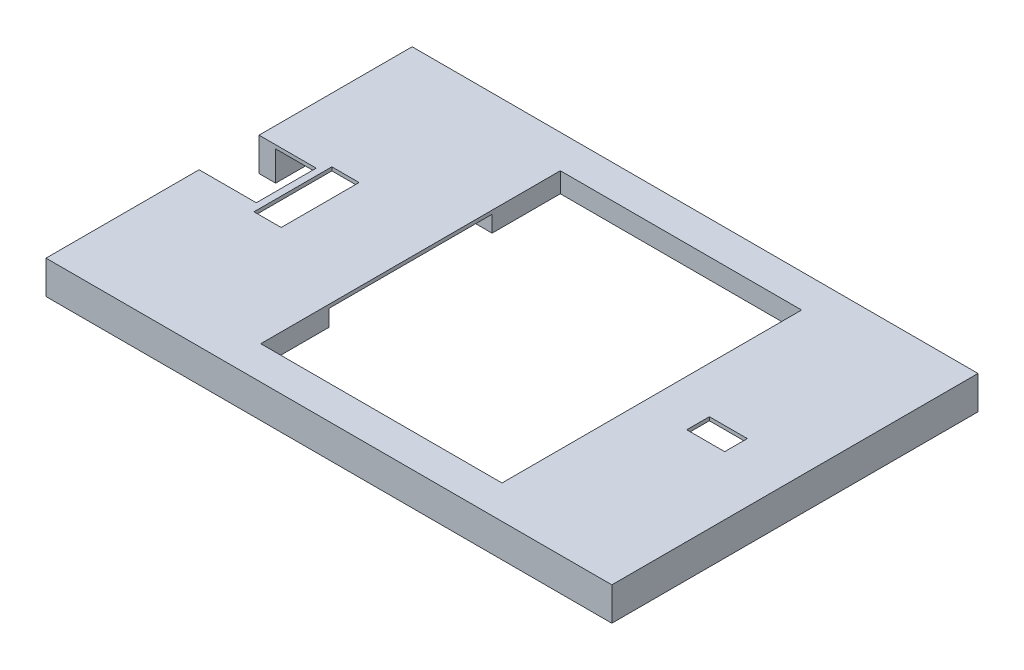
SolidWorks part; units mm, degrees
ref_plane "Front Plane" through (0, 0, 0) normal (0, 0, 1) x (1, 0, 0)
ref_plane "Top Plane" through (0, 0, 0) normal (0, 1, 0) x (1, 0, 0)
ref_plane "Right Plane" through (0, 0, 0) normal (1, 0, 0) x (0, 0, -1)
sketch "Sketch1" plane through (0, 0, 0) normal (0, 1, 0) x (1, 0, 0)
  line L0 (1.24, -32) -> (8.59, -32) construction
  line L1 (0, 0) -> (85, 0)
  line L2 (0, 0) -> (0, -55)
  line L3 (0, -55) -> (85, -55)
  line L4 (85, 0) -> (85, -55)
  line L5 (8.59, -23) -> (0, -23)
  line L6 (8.59, -23) -> (8.59, -32)
  line L7 (8.59, -32) -> (0, -32)
  line L8 (0, -23) -> (0, -32)
  line L9 (12.68, -32.35) -> (9.59, -32.35) construction
  line L10 (12.68, -32.35) -> (12.68, -22.65) construction
  line L11 (12.68, -22.65) -> (9.59, -22.65) construction
  line L12 (9.59, -32.35) -> (9.59, -22.65)
  line L13 (12.68, -22.65) -> (10.48, -22.65) construction
  line L14 (9.59, -22.65) -> (9.59, -21.65)
  line L15 (9.59, -21.65) -> (13.68, -21.65)
  line L16 (13.68, -21.65) -> (13.68, -33.35)
  line L17 (13.68, -33.35) -> (9.59, -33.35)
  line L18 (9.59, -33.35) -> (9.59, -32.35)
  line L19 (76.15, -25.8) -> (70.45, -25.8) construction
  line L20 (76.15, -25.8) -> (70.45, -25.8)
  line L21 (76.15, -25.8) -> (76.15, -29.2)
  line L22 (76.15, -29.2) -> (70.45, -29.2)
  line L23 (70.45, -25.8) -> (70.45, -29.2)
  line L24 (76.15, -29.2) -> (76.15, -25.8) construction
  line L25 (25.26, -36.5) -> (25.26, -18.5) construction
  line L26 (27.26, -5) -> (63.5, -5)
  line L27 (27.26, -5) -> (27.26, -50)
  line L28 (27.26, -50) -> (63.5, -50)
  line L29 (63.5, -5) -> (63.5, -50)
  line L30 (65.5, -31.75) -> (65.5, -36.5) construction
  dimension "D1" = 85
  dimension "D2" = 55
  dimension "D3" = 1
  dimension "D4" = 1
  dimension "D5" = 1
  dimension "D6" = 1
  dimension "D7" = 5
  dimension "D8" = 5
  dimension "D9" = 2
  dimension "D10" = 2
extrude "Boss-Extrude1" add sketch "Sketch1" along normal blind 3 contours L6 L7 L2 L3 L4 L1 L5 L23 L20 L21 L22 L17 L18 L12 L14 L15 L16 L26 L29 L28 L27
sketch "Sketch3" plane through (63.5, 0, 0) normal (-1, 0, 0) x (0, 0, 1)
  line L0 (36.5, 0.3152) -> (37.75, 0.3152) construction
  line L1 (31.75, 0.3152) -> (36.5, 0.3152) construction
  line L2 (18.5, 0.3152) -> (23.13, 0.3152) construction
  line L3 (17.25, 0.3152) -> (18.5, 0.3152) construction
  line L4 (36.5, 0.3152) -> (37.75, 0.3152) construction
  line L5 (31.75, 0.3152) -> (36.5, 0.3152) construction
  line L6 (18.5, 0.3152) -> (23.13, 0.3152) construction
  line L7 (17.25, 0.3152) -> (18.5, 0.3152) construction
  line L8 (5, 0) -> (50, 0) construction
  line L9 (15.25, 0) -> (39.75, 0)
  line L10 (15.25, 0) -> (15.25, 2.4652)
  line L11 (15.25, 2.4652) -> (39.75, 2.4652)
  line L12 (39.75, 0) -> (39.75, 2.4652)
  line L13 (26.45, 1.9652) -> (22.65, 1.9652) construction
  line L14 (26.45, 1.9652) -> (22.65, 1.9652)
  dimension "D1" = 2
  dimension "D2" = 2
  dimension "D3" = 0.5
extrude "Cut-Extrude1" cut sketch "Sketch3" against normal blind 19 and the other way blind 61
sketch "Sketch4" plane through (0, 0, 0) normal (0, -1, 0) x (1, 0, 0)
  line L0 (2.5, 32) -> (0, 32) construction
  line L1 (2.5, 23) -> (0, 23) construction
  line L2 (85, 0) -> (85, 55) construction
  line L3 (0, 55) -> (85, 55) construction
  line L4 (0, 32) -> (0, 55) construction
  line L5 (0, 0) -> (85, 0) construction
  line L6 (0, 0) -> (0, 23) construction
  line L7 (2.5, 2.5) -> (82.5, 2.5) construction
  line L8 (82.5, 2.5) -> (82.5, 52.5) construction
  line L9 (82.5, 52.5) -> (2.5, 52.5) construction
  line L10 (2.5, 52.5) -> (2.5, 2.5) construction
  line L11 (2.5, 32) -> (0, 32)
  line L12 (2.5, 23) -> (0, 23)
  line L13 (85, 0) -> (85, 55)
  line L14 (0, 55) -> (85, 55)
  line L15 (0, 32) -> (0, 55)
  line L16 (0, 0) -> (85, 0)
  line L17 (0, 0) -> (0, 23)
  line L18 (2.5, 2.5) -> (82.5, 2.5)
  line L19 (82.5, 2.5) -> (82.5, 52.5)
  line L20 (82.5, 52.5) -> (2.5, 52.5)
  line L21 (2.5, 52.5) -> (2.5, 2.5)
  line M3 (2.5, 15.25) -> (2.5, 23)
  line M4 (2.5, 23) -> (0, 23)
  line M5 (0, 23) -> (0, 0)
  line M6 (0, 0) -> (85, 0)
  line M7 (85, 0) -> (85, 55)
  line M8 (85, 55) -> (0, 55)
  line M9 (0, 55) -> (0, 32)
  line M10 (0, 32) -> (2.5, 32)
  line M11 (2.5, 32) -> (2.5, 39.75)
  line M17 (82.5, 39.75) -> (82.5, 15.25)
extrude "Boss-Extrude2" add sketch "Sketch4" along normal blind 2 contours L21 L20 L19 L18 M17 M3 M4 M5 M6 M7 M8 M9 M10 M11
